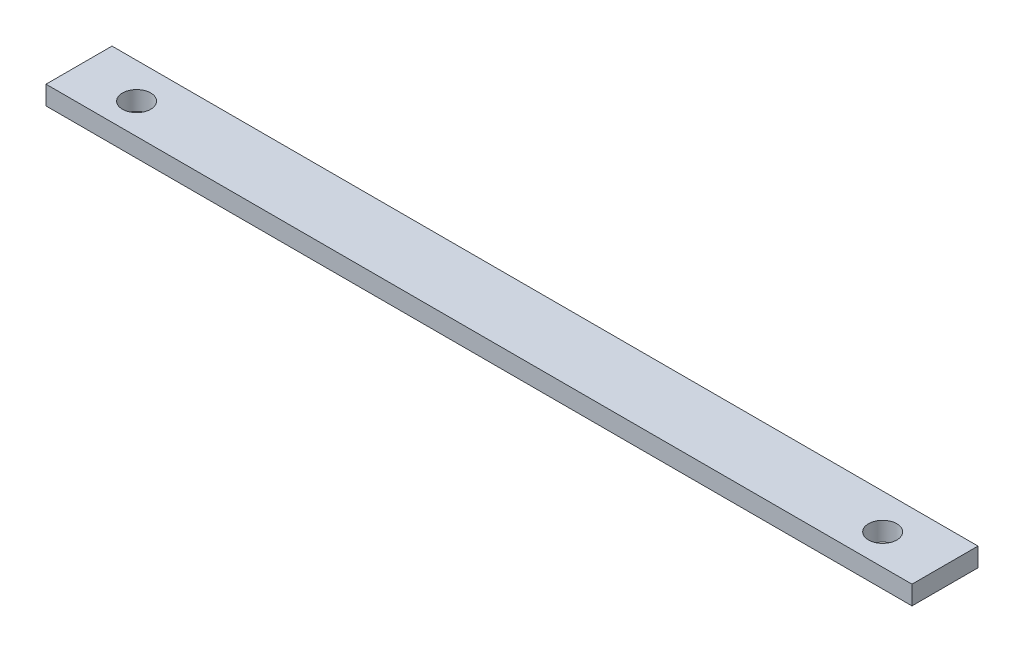
SolidWorks part; units mm, degrees
ref_plane "Front Plane" through (0, 0, 0) normal (0, 0, 1) x (1, 0, 0)
ref_plane "Top Plane" through (0, 0, 0) normal (0, 1, 0) x (1, 0, 0)
ref_plane "Right Plane" through (0, 0, 0) normal (1, 0, 0) x (0, 0, -1)
sketch "Sketch1" plane through (0, 0, 0) normal (0, 1, 0) x (1, 0, 0)
  line L1 (-91.8333, -7) -> (91.8333, -7)
  line L2 (-91.8333, -7) -> (-91.8333, 7)
  line L3 (-91.8333, 7) -> (91.8333, 7)
  line L4 (91.8333, -7) -> (91.8333, 7)
  line L5 (-91.8333, -7) -> (91.8333, 7) construction
  line L6 (-91.8333, 7) -> (91.8333, -7) construction
  point P0 (0, 0)
  dimension "D1" = 183.6667
  dimension "D2" = 14
extrude "Boss-Extrude1" add sketch "Sketch1" along normal blind 4
sketch "Sketch2" plane through (0, 4, 0) normal (0, 1, 0) x (1, 0, 0)
  line L0 (0, 7) -> (0, -7) construction
  line L1 (-91.8333, -7) -> (91.8333, -7) construction
  circle A0 centre (79.1167, -0.5) radius 3
  circle A1 centre (-79.1167, -0.5) radius 3
  point P9 (0, 0)
  dimension "D1" = 6
extrude "Cut-Extrude1" cut sketch "Sketch2" against normal through all
equation "\"D1@Sketch1\"=(551mm/3)"
